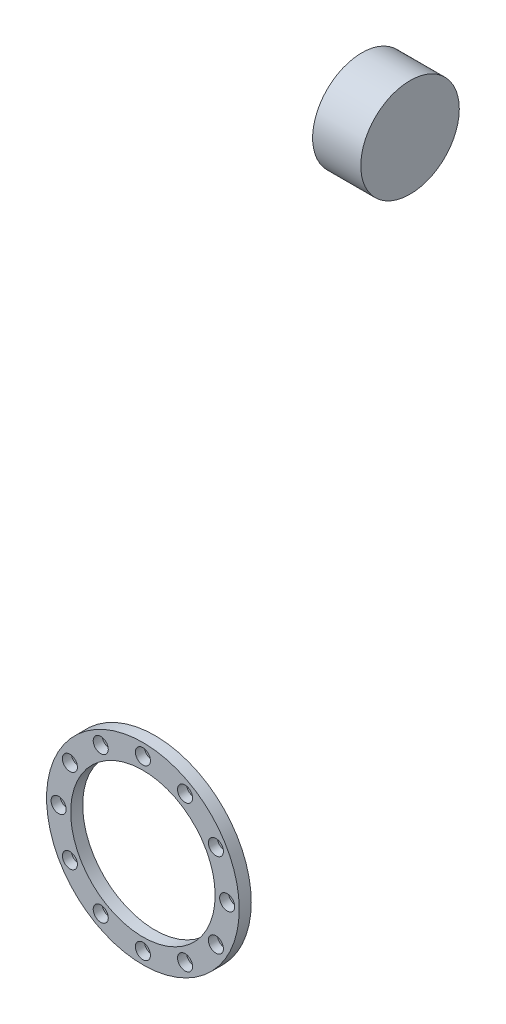
SolidWorks part; units mm, degrees
ref_plane "Front Plane" through (0, 0, 0) normal (0, 0, 1) x (1, 0, 0)
ref_plane "Top Plane" through (0, 0, 0) normal (0, 1, 0) x (1, 0, 0)
ref_plane "Right Plane" through (0, 0, 0) normal (1, 0, 0) x (0, 0, -1)
sketch "Sketch1" plane through (0, 0, 0) normal (0, 0, 1) x (1, 0, 0)
  circle A0 centre (0, 0) radius 101.6
  circle A1 centre (0, 0) radius 76.2
  dimension "D1" = 152.4
  dimension "D2" = 203.2
extrude "Boss-Extrude1" add sketch "Sketch1" along normal blind 12.7
hole_wizard "CBORE for 3/8 Socket Head Cap Screw1" positions "Sketch2" profile "Sketch4" counterbore size "3/8" standard "ANSI Inch" end condition through all
sketch "Sketch2" plane through (0, 0, 12.7) normal (0, 0, 1) x (1, 0, 0)
  line L0 (0, 76.2) -> (0, 101.6) construction
  circle A0 centre (0, 0) radius 76.2 construction
  circle A1 centre (0, 0) radius 101.6 construction
  point P0 (0, 88.9)
sketch "Sketch4" plane through (0, 88.9, 12.7) normal (1, 0, 0) x (0, -1, 0)
  line L0 (0, 0) -> (0, 12.7)
  line L1 (0, 12.7) -> (5.0419, 12.7)
  line L3 (5.0419, 12.7) -> (5.0419, 9.525)
  line L4 (5.0419, 9.525) -> (7.9375, 9.525)
  line L5 (7.9375, 9.525) -> (7.9375, 0)
  line L7 (7.9375, 0) -> (0, 0)
  line L11 (0, -6.35) -> (0, 107.95) construction
  dimension "Thru Hole Dia." = 10.0838
  dimension "Thru Hole Depth" = 12.7
  dimension "C'Bore Dia." = 15.875
  dimension "C'Bore Depth" = 9.525
pattern_circular "CirPattern1" count 12 over 360 about axis through (0, 0, 0) along (0, 0, 1) of "CBORE for 3/8 Socket Head Cap Screw1"
sketch "Sketch5" plane through (0, 0, 0) normal (1, 0, 0) x (0, 0, -1)
  circle A0 centre (243.6537, 538.7249) radius 51.9454
extrude "Boss-Extrude2" add sketch "Sketch5" along normal mid plane 50.8 separate body
